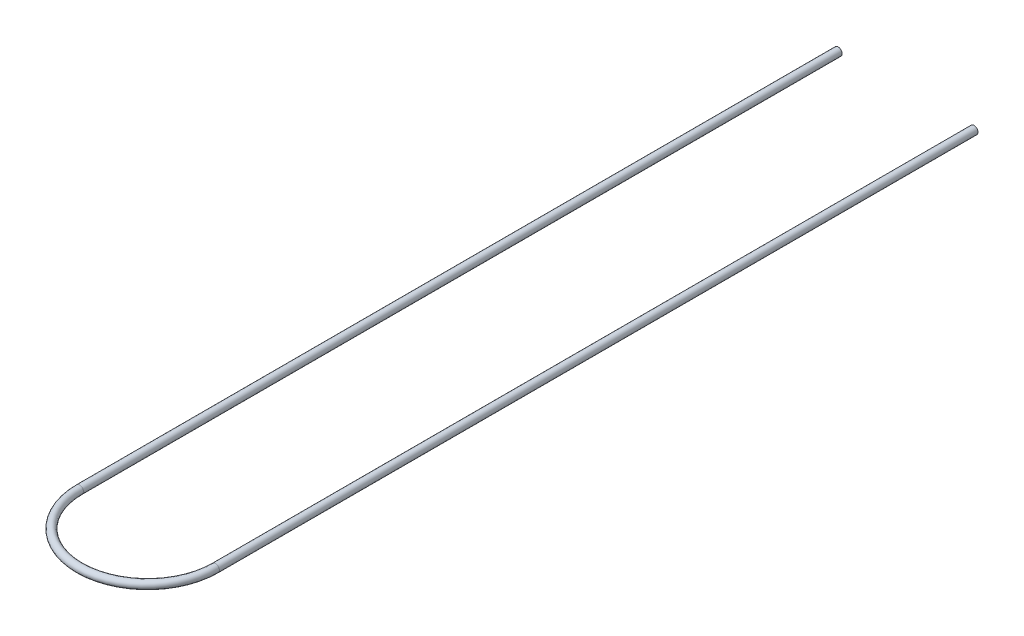
SolidWorks part; units mm, degrees
ref_plane "Front Plane" through (0, 0, 0) normal (0, 0, 1) x (1, 0, 0)
ref_plane "Top Plane" through (0, 0, 0) normal (0, 1, 0) x (1, 0, 0)
ref_plane "Right Plane" through (0, 0, 0) normal (1, 0, 0) x (0, 0, -1)
sketch "Sketch1" plane through (0, 0, 0) normal (0, 1, 0) x (1, 0, 0)
  line L0 (343.39, -300) -> (343.39, -2440)
  line L2 (-40, -300) -> (-40, -2440)
  arc A0 (-40, -2440) -> (343.39, -2440) centre (151.695, -2440) ccw
  dimension "D1" = 2140
  dimension "D2" = 383.39
ref_plane "Plane1" through (343.39, 0, 300) normal (0, 0, -1) x (-1, 0, 0)
sketch "Sketch2" plane through (343.39, 0, 300) normal (0, 0, -1) x (-1, 0, 0)
  circle A0 centre (0, 0) radius 9.95
  circle A1 centre (0, 0) radius 11.1
  dimension "D1" = 22.2
  dimension "D2" = 19.9
sweep "Sweep1" add profiles "Sketch2" path "Sketch1"
